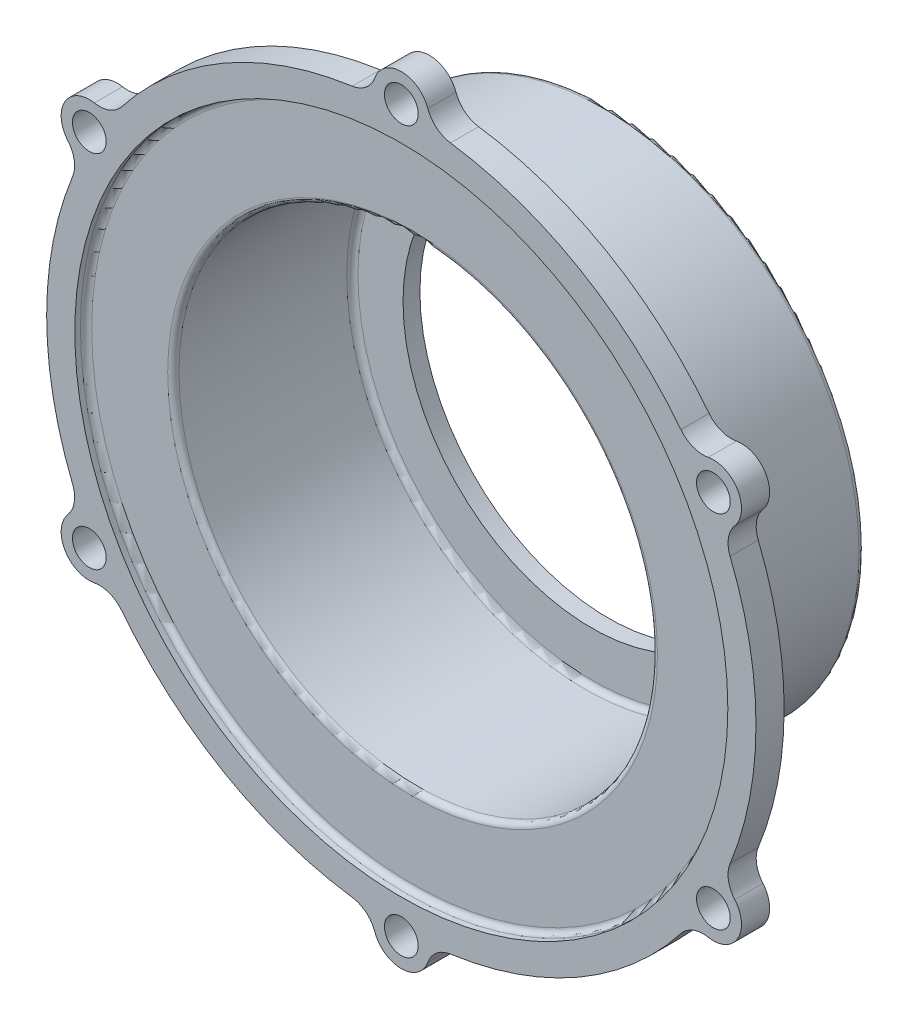
SolidWorks part; units mm, degrees
material "7075-T6 (SN)"
ref_plane "Front Plane" through (0, 0, 0) normal (0, 0, 1) x (1, 0, 0)
ref_plane "Top Plane" through (0, 0, 0) normal (0, 1, 0) x (1, 0, 0)
ref_plane "Right Plane" through (0, 0, 0) normal (1, 0, 0) x (0, 0, -1)
sketch "Sketch2" plane through (0, 0, 0) normal (1, 0, 0) x (0, 0, -1)
  line L0 (-59.9535, 0) -> (59.9535, 0) construction
  line L1 (10.3257, 42.5) -> (42.1257, 42.5)
  line L2 (8.3257, 63) -> (8.3257, 58)
  line L3 (42.1257, 42.5) -> (42.1257, 33.5)
  line L4 (13.3257, 63) -> (13.3257, 45.5)
  line L5 (13.3257, 45.5) -> (45.1257, 45.5)
  line L6 (45.1257, 45.5) -> (45.1257, 33.5)
  line L7 (8.3257, 63) -> (13.3257, 63)
  line L8 (42.1257, 33.5) -> (45.1257, 33.5)
  line L9 (8.3257, 58) -> (10.3257, 58)
  line L10 (10.3257, 58) -> (10.3257, 42.5)
  point P4 (0, 0)
  dimension "D1" = 42.5
  dimension "D2" = 33.5
  dimension "D3" = 31.8
  dimension "D4" = 63
  dimension "D6" = 5
  dimension "D5" = 3
  dimension "D7" = 3
  dimension "D8" = 5
  dimension "D9" = 2
revolve "Revolve1" add sketch "Sketch2" angle 360 about L0
sketch "Sketch3" plane through (0, 0, -8.3257) normal (0, 0, 1) x (1, 0, 0)
  line L4 (0, 63) -> (0, 64) construction
  line L35 (0, 64) -> (0, 63) construction
  circle A77 centre (0, 64) radius 3
  arc A154 (4.8569, 62.8125) -> (-4.8569, 62.8125) centre (0, 64) ccw
  arc A156 (56.8257, 27.2) -> (51.9688, 35.6125) centre (55.4256, 32) ccw
  arc A160 (51.9688, -35.6125) -> (56.8257, -27.2) centre (55.4256, -32) ccw
  arc A164 (-4.8569, -62.8125) -> (4.8569, -62.8125) centre (0, -64) ccw
  arc A166 (-56.8257, -27.2) -> (-51.9688, -35.6125) centre (-55.4256, -32) ccw
  arc A168 (-51.9688, 35.6125) -> (-56.8257, 27.2) centre (-55.4256, 32) ccw
  arc A170 (-4.8569, 62.8125) -> (-51.9688, 35.6125) centre (0, 0) ccw
  circle A171 centre (55.4256, 32) radius 3
  arc A172 (51.9688, 35.6125) -> (4.8569, 62.8125) centre (0, 0) ccw
  arc A173 (56.8257, -27.2) -> (56.8257, 27.2) centre (0, 0) ccw
  circle A174 centre (55.4256, -32) radius 3
  circle A175 centre (0, -64) radius 3
  arc A176 (4.8569, -62.8125) -> (51.9688, -35.6125) centre (0, 0) ccw
  arc A177 (-51.9688, -35.6125) -> (-4.8569, -62.8125) centre (0, 0) ccw
  circle A178 centre (-55.4256, -32) radius 3
  arc A179 (-56.8257, 27.2) -> (-56.8257, -27.2) centre (0, 0) ccw
  circle A180 centre (-55.4256, 32) radius 3
  circle A181 centre (-55.4256, 32) radius 3 [skipped]
  circle A182 centre (-55.4256, -32) radius 3 [skipped]
  circle A183 centre (0, -64) radius 3 [skipped]
  circle A184 centre (55.4256, -32) radius 3 [skipped]
  circle A185 centre (55.4256, 32) radius 3 [skipped]
  point P21 (0, 0)
  point P28 (0, 0)
  dimension "D1" = 6
extrude "Boss-Extrude1" add sketch "Sketch3" against normal up to surface (5 mm away)
sketch "Sketch4" plane through (0, 0, -13.3257) normal (0, 0, -1) x (-1, 0, 0)
  circle A25 centre (55.4256, 32) radius 3
  circle A26 centre (55.4256, -32) radius 3
  circle A27 centre (0, -64) radius 3
  circle A28 centre (-55.4256, -32) radius 3
  circle A29 centre (-55.4256, 32) radius 3
  circle A30 centre (0, 64) radius 3
extrude "Cut-Extrude1" cut sketch "Sketch4" against normal up to surface (5 mm away) contours A30 up to face at (0, 0, -8.3257)
fillet "Fillet1" radius 1 5 edges at (42.5, 0, -42.1257) (45.5, 0, -45.1257) (45.5, 0, -13.3257) (58, 0, -10.3257) (42.5, 0, -10.3257)
fillet "Fillet3" radius 5 12 edges at (51.9688, 35.6125, -10.8257) (56.8257, 27.2, -10.8257) (56.8257, -27.2, -10.8257) (51.9688, -35.6125, -10.8257) (4.8569, -62.8125, -10.8257) (-4.8569, -62.8125, -10.8257) (-51.9688, -35.6125, -10.8257) (-56.8257, -27.2, -10.8257) (-56.8257, 27.2, -10.8257) (-51.9688, 35.6125, -10.8257) (-4.8569, 62.8125, -10.8257) (4.8569, 62.8125, -10.8257)
sketch "Sketch6" plane through (0, 0, -13.3257) normal (0, 0, -1) x (-1, 0, 0)
  circle A0 centre (0, 64) radius 3
  circle A1 centre (55.4256, 32) radius 3
  circle A2 centre (55.4256, -32) radius 3
  circle A3 centre (0, -64) radius 3
  circle A4 centre (-55.4256, -32) radius 3
  circle A5 centre (-55.4256, 32) radius 3
  point P15 (0, 0)
extrude "Cut-Extrude2" cut sketch "Sketch6" against normal blind 10
